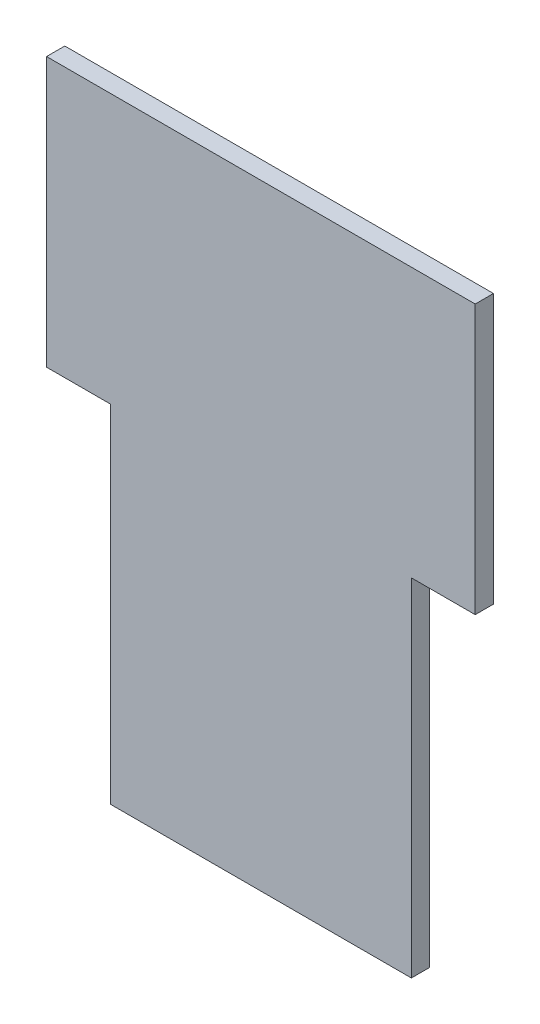
SolidWorks part; units mm, degrees
material "Beech"
ref_plane "Front Plane" through (0, 0, 0) normal (0, 0, 1) x (1, 0, 0)
ref_plane "Top Plane" through (0, 0, 0) normal (0, 1, 0) x (1, 0, 0)
ref_plane "Right Plane" through (0, 0, 0) normal (1, 0, 0) x (0, 0, -1)
sketch "Sketch2" plane through (0, 0, 0) normal (0, 0, 1) x (1, 0, 0)
  line L0 (0, 365.7807) -> (0, -527.0993) construction
  line L1 (-235, 310.6322) -> (235, 310.6322)
  line L2 (235, 310.6322) -> (235, 15.6322)
  line L3 (235, 15.6322) -> (165, 15.6322)
  line L4 (165, 15.6322) -> (165, -364.3678)
  line L5 (-165, 15.6322) -> (-165, -364.3678)
  line L6 (-235, 15.6322) -> (-165, 15.6322)
  line L7 (-235, 310.6322) -> (-235, 15.6322)
  line L8 (-165, -364.3678) -> (165, -364.3678)
  point P12 (0, 310.6322)
  dimension "D2" = 295
  dimension "D3" = 70
  dimension "D4" = 380
  dimension "D5" = 470
extrude "Boss-Extrude1" add sketch "Sketch2" along normal blind 20
